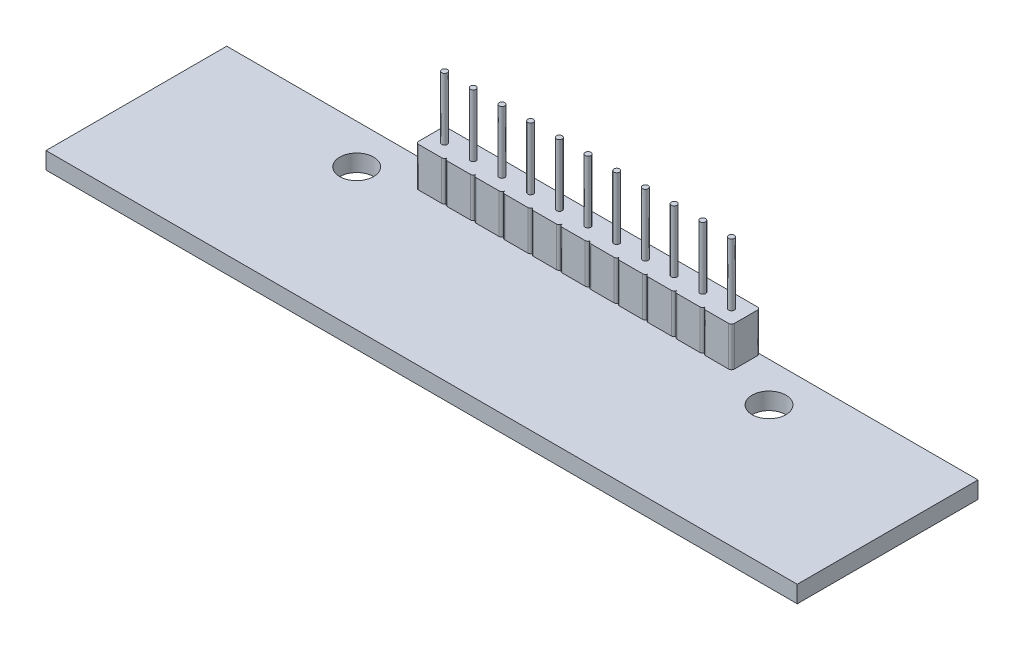
SolidWorks part; units mm, degrees
ref_plane "Front Plane" through (0, 0, 0) normal (0, 0, 1) x (1, 0, 0)
ref_plane "Top Plane" through (0, 0, 0) normal (0, 1, 0) x (1, 0, 0)
ref_plane "Right Plane" through (0, 0, 0) normal (1, 0, 0) x (0, 0, -1)
sketch "Sketch1" plane through (0, 0, 0) normal (0, 1, 0) x (1, 0, 0)
  line L1 (-33.25, -8) -> (33.25, -8)
  line L2 (-33.25, -8) -> (-33.25, 8)
  line L3 (-33.25, 8) -> (33.25, 8)
  line L4 (33.25, -8) -> (33.25, 8)
  line L5 (-33.25, -8) -> (33.25, 8) construction
  line L6 (-33.25, 8) -> (33.25, -8) construction
  point P0 (0, 0)
  dimension "D1" = 16
  dimension "D2" = 66.5
extrude "Boss-Extrude1" add sketch "Sketch1" along normal blind 1.5
sketch "Sketch2" plane through (0, 1.5, 0) normal (0, 1, 0) x (1, 0, 0)
  line L0 (-18.25, 4.5) -> (18.25, 4.5)
  line L3 (33.25, 8) -> (-33.25, 8) construction
  circle A0 centre (-18.25, 4.5) radius 1.5
  circle A1 centre (18.25, 4.5) radius 1.5
  point P4 (0, 4.5)
  dimension "D1" = 3
  dimension "D2" = 2
  dimension "D3" = 33.5
extrude "Cut-Extrude1" cut sketch "Sketch2" against normal through all
sketch "Sketch3" plane through (0, 0, 0) normal (0, -1, 0) x (1, 0, 0)
  line L0 (-33.25, 8) -> (33.25, 8) construction
  line L1 (-29.25, 6.3) -> (-26.45, 6.3)
  line L2 (-29.25, 6.3) -> (-29.25, 3)
  line L3 (-29.25, 3) -> (-26.45, 3)
  line L4 (-26.45, 6.3) -> (-26.45, 3)
  line L5 (-29.25, 6.3) -> (-26.45, 3) construction
  line L6 (-29.25, 3) -> (-26.45, 6.3) construction
  line L7 (-21.2929, 6.3) -> (-21.2929, 3)
  line L8 (-21.2929, 3) -> (-18.4929, 6.3) construction
  line L9 (-21.2929, 6.3) -> (-18.4929, 3) construction
  line L10 (-18.4929, 6.3) -> (-18.4929, 3)
  line L11 (-21.2929, 3) -> (-18.4929, 3)
  line L12 (-21.2929, 6.3) -> (-18.4929, 6.3)
  line L13 (-13.3357, 6.3) -> (-13.3357, 3)
  line L14 (-13.3357, 3) -> (-10.5357, 6.3) construction
  line L15 (-13.3357, 6.3) -> (-10.5357, 3) construction
  line L16 (-10.5357, 6.3) -> (-10.5357, 3)
  line L17 (-13.3357, 3) -> (-10.5357, 3)
  line L18 (-13.3357, 6.3) -> (-10.5357, 6.3)
  line L19 (-5.3786, 6.3) -> (-5.3786, 3)
  line L20 (-5.3786, 3) -> (-2.5786, 6.3) construction
  line L21 (-5.3786, 6.3) -> (-2.5786, 3) construction
  line L22 (-2.5786, 6.3) -> (-2.5786, 3)
  line L23 (-5.3786, 3) -> (-2.5786, 3)
  line L24 (-5.3786, 6.3) -> (-2.5786, 6.3)
  line L25 (2.5786, 6.3) -> (2.5786, 3)
  line L26 (2.5786, 3) -> (5.3786, 6.3) construction
  line L27 (2.5786, 6.3) -> (5.3786, 3) construction
  line L28 (5.3786, 6.3) -> (5.3786, 3)
  line L29 (2.5786, 3) -> (5.3786, 3)
  line L30 (2.5786, 6.3) -> (5.3786, 6.3)
  line L31 (10.5357, 6.3) -> (10.5357, 3)
  line L32 (10.5357, 3) -> (13.3357, 6.3) construction
  line L33 (10.5357, 6.3) -> (13.3357, 3) construction
  line L34 (13.3357, 6.3) -> (13.3357, 3)
  line L35 (10.5357, 3) -> (13.3357, 3)
  line L36 (10.5357, 6.3) -> (13.3357, 6.3)
  line L37 (18.4929, 6.3) -> (18.4929, 3)
  line L38 (18.4929, 3) -> (21.2929, 6.3) construction
  line L39 (18.4929, 6.3) -> (21.2929, 3) construction
  line L40 (21.2929, 6.3) -> (21.2929, 3)
  line L41 (18.4929, 3) -> (21.2929, 3)
  line L42 (18.4929, 6.3) -> (21.2929, 6.3)
  line L43 (26.45, 6.3) -> (26.45, 3)
  line L44 (26.45, 3) -> (29.25, 6.3) construction
  line L45 (26.45, 6.3) -> (29.25, 3) construction
  line L46 (29.25, 6.3) -> (29.25, 3)
  line L47 (26.45, 3) -> (29.25, 3)
  line L48 (26.45, 6.3) -> (29.25, 6.3)
  line L49 (-27.85, 4.65) -> (27.85, 4.65) construction
  point P0 (-27.85, 4.65)
  point P37 (0, 0)
  point P38 (27.4991, 4.65)
  point P39 (0, 0)
  point P40 (0, 4.65)
  dimension "D1" = 2.8
  dimension "D2" = 3.3
  dimension "D3" = 5
  dimension "D5" = 58.5
  dimension "D4" = 8
extrude "Boss-Extrude2" add sketch "Sketch3" along normal blind 1.5 separate body
sketch "Sketch5" plane through (0, 1.5, 0) normal (0, 1, 0) x (1, 0, 0)
  line L0 (33.25, 8) -> (-33.25, 8) construction
  line L1 (-1.02, 8) -> (1.02, 8)
  line L2 (-1.27, 7.75) -> (-1.27, 5.71)
  line L3 (-1.02, 5.46) -> (1.02, 5.46)
  line L4 (1.27, 7.75) -> (1.27, 5.71)
  line L5 (-1.27, 8) -> (1.27, 5.46) construction
  line L6 (-1.27, 5.46) -> (1.27, 8) construction
  line L7 (1.27, 7.75) -> (1.27, 5.71)
  line L8 (1.52, 8) -> (3.56, 8)
  line L9 (3.81, 7.75) -> (3.81, 5.71)
  line L10 (1.52, 5.46) -> (3.56, 5.46)
  line L11 (3.81, 7.75) -> (3.81, 5.71)
  line L12 (4.06, 8) -> (6.1, 8)
  line L13 (6.35, 7.75) -> (6.35, 5.71)
  line L14 (4.06, 5.46) -> (6.1, 5.46)
  line L15 (6.35, 7.75) -> (6.35, 5.71)
  line L16 (6.6, 8) -> (8.64, 8)
  line L17 (8.89, 7.75) -> (8.89, 5.71)
  line L18 (6.6, 5.46) -> (8.64, 5.46)
  line L19 (8.89, 7.75) -> (8.89, 5.71)
  line L20 (9.14, 8) -> (11.18, 8)
  line L21 (11.43, 7.75) -> (11.43, 5.71)
  line L22 (9.14, 5.46) -> (11.18, 5.46)
  line L23 (11.43, 7.75) -> (11.43, 5.71)
  line L24 (11.68, 8) -> (13.72, 8)
  line L25 (13.97, 7.75) -> (13.97, 5.71)
  line L26 (11.68, 5.46) -> (13.72, 5.46)
  line L27 (-3.81, 7.75) -> (-3.81, 5.71)
  line L28 (-3.56, 8) -> (-1.52, 8)
  line L29 (-1.27, 7.75) -> (-1.27, 5.71)
  line L30 (-3.56, 5.46) -> (-1.52, 5.46)
  line L31 (-6.35, 7.75) -> (-6.35, 5.71)
  line L32 (-6.1, 8) -> (-4.06, 8)
  line L33 (-3.81, 7.75) -> (-3.81, 5.71)
  line L34 (-6.1, 5.46) -> (-4.06, 5.46)
  line L35 (-8.89, 7.75) -> (-8.89, 5.71)
  line L36 (-8.64, 8) -> (-6.6, 8)
  line L37 (-6.35, 7.75) -> (-6.35, 5.71)
  line L38 (-8.64, 5.46) -> (-6.6, 5.46)
  line L39 (-11.43, 7.75) -> (-11.43, 5.71)
  line L40 (-11.18, 8) -> (-9.14, 8)
  line L41 (-8.89, 7.75) -> (-8.89, 5.71)
  line L42 (-11.18, 5.46) -> (-9.14, 5.46)
  line L43 (-13.97, 7.75) -> (-13.97, 5.71)
  line L44 (-13.72, 8) -> (-11.68, 8)
  line L45 (-11.43, 7.75) -> (-11.43, 5.71)
  line L46 (-13.72, 5.46) -> (-11.68, 5.46)
  arc A0 (-1.27, 5.71) -> (-1.02, 5.46) centre (-1.02, 5.71) ccw
  arc A1 (1.02, 5.46) -> (1.27, 5.71) centre (1.02, 5.71) ccw
  arc A2 (1.02, 8) -> (1.27, 7.75) centre (1.02, 7.75) cw
  arc A3 (-1.02, 8) -> (-1.27, 7.75) centre (-1.02, 7.75) ccw
  arc A4 (1.52, 8) -> (1.27, 7.75) centre (1.52, 7.75) ccw
  arc A5 (1.27, 5.71) -> (1.52, 5.46) centre (1.52, 5.71) ccw
  arc A6 (3.56, 8) -> (3.81, 7.75) centre (3.56, 7.75) cw
  arc A7 (3.56, 5.46) -> (3.81, 5.71) centre (3.56, 5.71) ccw
  arc A8 (4.06, 8) -> (3.81, 7.75) centre (4.06, 7.75) ccw
  arc A9 (3.81, 5.71) -> (4.06, 5.46) centre (4.06, 5.71) ccw
  arc A10 (6.1, 8) -> (6.35, 7.75) centre (6.1, 7.75) cw
  arc A11 (6.1, 5.46) -> (6.35, 5.71) centre (6.1, 5.71) ccw
  arc A12 (6.6, 8) -> (6.35, 7.75) centre (6.6, 7.75) ccw
  arc A13 (6.35, 5.71) -> (6.6, 5.46) centre (6.6, 5.71) ccw
  arc A14 (8.64, 8) -> (8.89, 7.75) centre (8.64, 7.75) cw
  arc A15 (8.64, 5.46) -> (8.89, 5.71) centre (8.64, 5.71) ccw
  arc A16 (9.14, 8) -> (8.89, 7.75) centre (9.14, 7.75) ccw
  arc A17 (8.89, 5.71) -> (9.14, 5.46) centre (9.14, 5.71) ccw
  arc A18 (11.18, 8) -> (11.43, 7.75) centre (11.18, 7.75) cw
  arc A19 (11.18, 5.46) -> (11.43, 5.71) centre (11.18, 5.71) ccw
  arc A20 (11.68, 8) -> (11.43, 7.75) centre (11.68, 7.75) ccw
  arc A21 (11.43, 5.71) -> (11.68, 5.46) centre (11.68, 5.71) ccw
  arc A22 (13.72, 8) -> (13.97, 7.75) centre (13.72, 7.75) cw
  arc A23 (13.72, 5.46) -> (13.97, 5.71) centre (13.72, 5.71) ccw
  arc A24 (-3.56, 8) -> (-3.81, 7.75) centre (-3.56, 7.75) ccw
  arc A25 (-3.81, 5.71) -> (-3.56, 5.46) centre (-3.56, 5.71) ccw
  arc A26 (-1.52, 8) -> (-1.27, 7.75) centre (-1.52, 7.75) cw
  arc A27 (-1.52, 5.46) -> (-1.27, 5.71) centre (-1.52, 5.71) ccw
  arc A28 (-6.1, 8) -> (-6.35, 7.75) centre (-6.1, 7.75) ccw
  arc A29 (-6.35, 5.71) -> (-6.1, 5.46) centre (-6.1, 5.71) ccw
  arc A30 (-4.06, 8) -> (-3.81, 7.75) centre (-4.06, 7.75) cw
  arc A31 (-4.06, 5.46) -> (-3.81, 5.71) centre (-4.06, 5.71) ccw
  arc A32 (-8.64, 8) -> (-8.89, 7.75) centre (-8.64, 7.75) ccw
  arc A33 (-8.89, 5.71) -> (-8.64, 5.46) centre (-8.64, 5.71) ccw
  arc A34 (-6.6, 8) -> (-6.35, 7.75) centre (-6.6, 7.75) cw
  arc A35 (-6.6, 5.46) -> (-6.35, 5.71) centre (-6.6, 5.71) ccw
  arc A36 (-11.18, 8) -> (-11.43, 7.75) centre (-11.18, 7.75) ccw
  arc A37 (-11.43, 5.71) -> (-11.18, 5.46) centre (-11.18, 5.71) ccw
  arc A38 (-9.14, 8) -> (-8.89, 7.75) centre (-9.14, 7.75) cw
  arc A39 (-9.14, 5.46) -> (-8.89, 5.71) centre (-9.14, 5.71) ccw
  arc A40 (-13.72, 8) -> (-13.97, 7.75) centre (-13.72, 7.75) ccw
  arc A41 (-13.97, 5.71) -> (-13.72, 5.46) centre (-13.72, 5.71) ccw
  arc A42 (-11.68, 8) -> (-11.43, 7.75) centre (-11.68, 7.75) cw
  arc A43 (-11.68, 5.46) -> (-11.43, 5.71) centre (-11.68, 5.71) ccw
  point P0 (0, 6.73)
  line M21 (33.25, 8) -> (-33.25, 8)
  dimension "D3" = 0.25
  dimension "D1" = 2.54
  dimension "D2" = 2.54
  dimension "D4" = 6
  dimension "D5" = 6
extrude "Boss-Extrude3" add sketch "Sketch5" along normal blind 3.5 separate body contours L46 A43 L39 A42 A40 L43 A41 M21 | L42 A39 L35 A38 A36 L39 A37 M21 | L38 A35 L31 A34 A32 L35 A33 M21 | L34 A31 L27 A30 A28 L31 A29 M21 | L30 A27 L2 A26 A24 L27 A25 M21 | A3 L2 A0 L3 A1 L4 A2 M21 | L10 A7 L9 A6 A4 L4 A5 M21 | L14 A11 L13 A10 A8 L9 A9 M21 | L18 A15 L17 A14 A12 L13 A13 M21 | L22 A19 L21 A18 A16 L17 A17 M21 | L26 A23 L25 A22 A20 L21 A21 M21
sketch "Sketch7" plane through (0, 5, 0) normal (0, 1, 0) x (1, 0, 0)
  circle A0 centre (0, 6.73) radius 0.25
  circle A1 centre (2.54, 6.73) radius 0.25
  circle A2 centre (5.08, 6.73) radius 0.25
  circle A3 centre (7.62, 6.73) radius 0.25
  circle A4 centre (10.16, 6.73) radius 0.25
  circle A5 centre (12.7, 6.73) radius 0.25
  circle A6 centre (-2.54, 6.73) radius 0.25
  circle A7 centre (-5.08, 6.73) radius 0.25
  circle A8 centre (-7.62, 6.73) radius 0.25
  circle A9 centre (-10.16, 6.73) radius 0.25
  circle A10 centre (-12.7, 6.73) radius 0.25
  dimension "D1" = 0.5
  dimension "D4" = 2.54
  dimension "D5" = 2.54
  dimension "D2" = 6
  dimension "D3" = 6
extrude "Boss-Extrude4" add sketch "Sketch7" along normal blind 5.5 separate body
